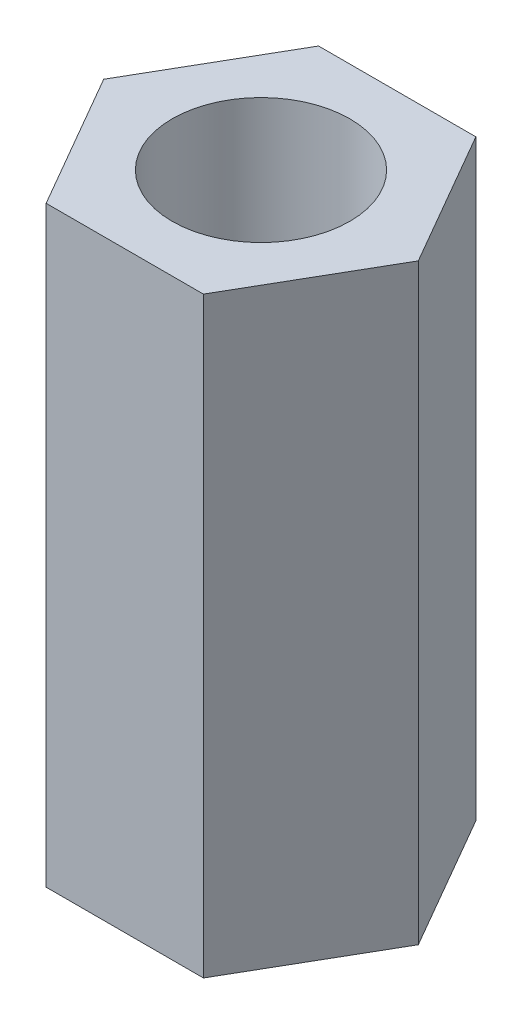
SolidWorks part; units mm, degrees
ref_plane "前视基准面" through (0, 0, 0) normal (0, 0, 1) x (1, 0, 0)
ref_plane "上视基准面" through (0, 0, 0) normal (0, 1, 0) x (1, 0, 0)
ref_plane "右视基准面" through (0, 0, 0) normal (1, 0, 0) x (0, 0, -1)
other "Configuration Table"
sketch "草图1" plane through (0, 0, 0) normal (0, 1, 0) x (1, 0, 0)
  line L1 (1.3279, -2.3) -> (2.6558, 0)
  line L2 (2.6558, 0) -> (1.3279, 2.3)
  line L3 (1.3279, 2.3) -> (-1.3279, 2.3)
  line L4 (-1.3279, 2.3) -> (-2.6558, 0)
  line L5 (-2.6558, 0) -> (-1.3279, -2.3)
  line L6 (-1.3279, -2.3) -> (1.3279, -2.3)
  circle A0 centre (0, 0) radius 1.5
  circle A1 centre (0, 0) radius 2.3 construction
  dimension "D2" = 3
  dimension "D1" = 4.6
extrude "凸台-拉伸1" add sketch "草图1" along normal blind 10
